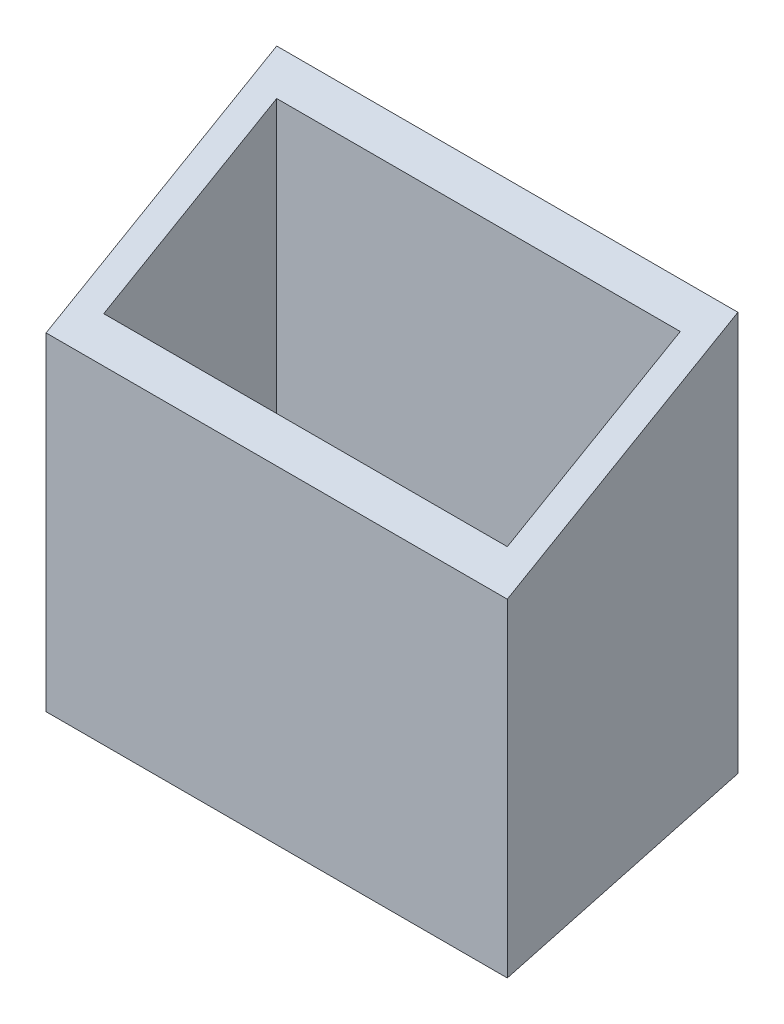
SolidWorks part; units mm, degrees
ref_plane "Front" through (0, 0, 0) normal (0, 0, 1) x (1, 0, 0)
ref_plane "Top" through (0, 0, 0) normal (0, 1, 0) x (1, 0, 0)
ref_plane "Right" through (0, 0, 0) normal (1, 0, 0) x (0, 0, -1)
sketch "Sketch1" plane through (0, 0, 0) normal (0, 1, 0) x (1, 0, 0)
  line L0 (-22.225, -9.525) -> (22.225, -9.525)
  line L1 (-25.4, 12.7) -> (25.4, 12.7)
  line L2 (-25.4, 12.7) -> (-25.4, -12.7)
  line L3 (-25.4, -12.7) -> (25.4, -12.7)
  line L4 (25.4, 12.7) -> (25.4, -12.7)
  line L5 (-25.4, 12.7) -> (25.4, -12.7) construction
  line L6 (-25.4, -12.7) -> (25.4, 12.7) construction
  line L7 (22.225, 9.525) -> (22.225, -9.525)
  line L8 (-22.225, 9.525) -> (22.225, 9.525)
  line L9 (-22.225, 9.525) -> (-22.225, -9.525)
  point P0 (0, 0)
  dimension "D1" = 50.8
  dimension "D2" = 25.4
  dimension "D3" = 3.175
extrude "Boss-Extrude1" add sketch "Sketch1" along normal blind 50.8
sketch "Sketch2" plane through (-25.4, 0, 0) normal (-1, 0, 0) x (0, 0, 1)
  line L0 (-12.7, 50.8) -> (12.7, 36.1353)
  line L2 (12.7, 50.8) -> (12.7, 0) construction
  line L7 (-12.7, 0) -> (12.7, 0)
  line L8 (12.7, 0) -> (12.7, 50.8)
  line L9 (12.7, 50.8) -> (-12.7, 50.8)
  line L10 (-12.7, 50.8) -> (-12.7, 0)
  line L11 (-12.7, 0) -> (12.7, 0)
  line L12 (12.7, 0) -> (12.7, 50.8)
  line L13 (12.7, 50.8) -> (-12.7, 50.8)
  line L14 (-12.7, 50.8) -> (-12.7, 0)
  line M7 (12.7, 0) -> (12.7, 50.8)
  line M8 (12.7, 50.8) -> (-12.7, 50.8)
  dimension "D2" = 30
  dimension "D1" = 0
extrude "Cut-Extrude1" cut sketch "Sketch2" against normal through all contours L0 M8 M7
sketch "Sketch3" plane through (25.4, 0, 0) normal (1, 0, 0) x (0, 0, -1)
  line L0 (-12.7, 0) -> (12.7, 6.8059)
  line L4 (12.7, 0) -> (12.7, 50.8)
  line L5 (12.7, 50.8) -> (-12.7, 36.1353)
  line L6 (-12.7, 36.1353) -> (-12.7, 0)
  line L7 (-12.7, 0) -> (12.7, 0)
  line L8 (12.7, 0) -> (12.7, 50.8)
  line L9 (12.7, 50.8) -> (-12.7, 36.1353)
  line L10 (-12.7, 36.1353) -> (-12.7, 0)
  line L11 (-12.7, 0) -> (12.7, 0)
  line M6 (12.7, 0) -> (12.7, 50.8)
  line M9 (-12.7, 0) -> (12.7, 0)
  dimension "D2" = 15
  dimension "D1" = 0
extrude "Cut-Extrude2" cut sketch "Sketch3" along direction (-1, 0, 0) on the side against the normal through all contours L0 M9 M6
